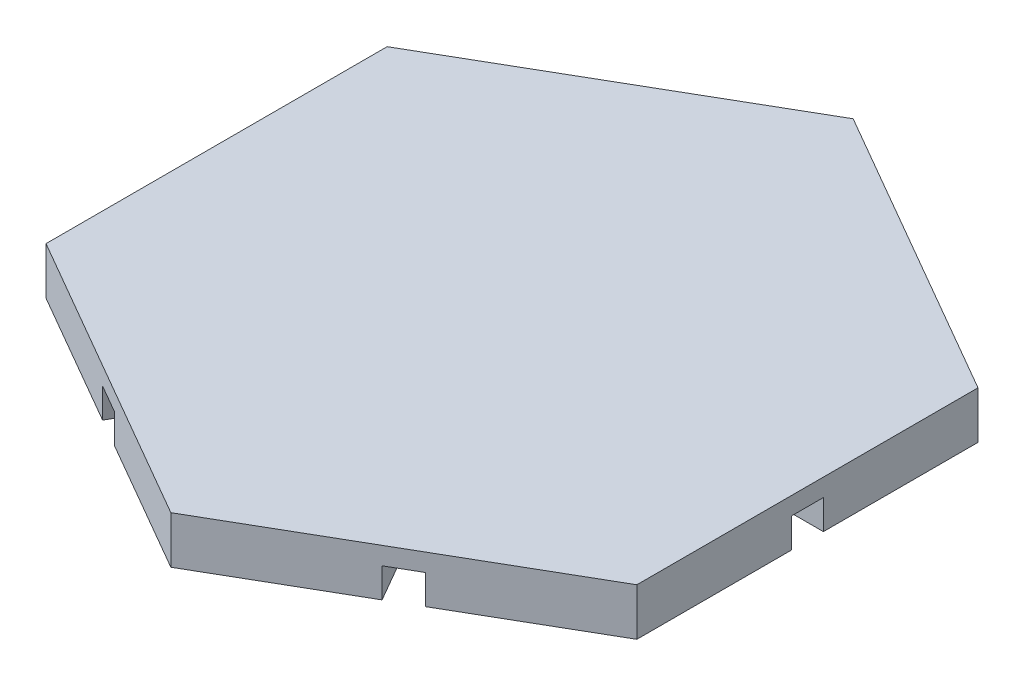
SolidWorks part; units mm, degrees
material "PET"
ref_plane "Front Plane" through (0, 0, 0) normal (0, 0, 1) x (1, 0, 0)
ref_plane "Top Plane" through (0, 0, 0) normal (0, 1, 0) x (1, 0, 0)
ref_plane "Right Plane" through (0, 0, 0) normal (1, 0, 0) x (0, 0, -1)
sketch "Sketch1" plane through (0, 0, 0) normal (0, 1, 0) x (1, 0, 0)
  line L0 (25, 43.3013) -> (-25, -43.3013) construction
  line L1 (0, 57.735) -> (-50, 28.8675)
  line L2 (-50, 28.8675) -> (-50, -28.8675)
  line L3 (-50, -28.8675) -> (0, -57.735)
  line L4 (0, -57.735) -> (50, -28.8675)
  line L5 (50, -28.8675) -> (50, 28.8675)
  line L6 (50, 28.8675) -> (0, 57.735)
  circle A0 centre (0, 0) radius 50 construction
  dimension "D2" = 100
extrude "Boss-Extrude1" add sketch "Sketch1" along normal blind 8
sketch "Sketch2" plane through (0, 0, 0) normal (0, -1, 0) x (1, 0, 0)
  line L0 (-25, 43.3013) -> (25, -43.3013)
  line L1 (-50, 28.8675) -> (0, 57.735) construction
  line L2 (50, -28.8675) -> (0, -57.735) construction
  line L3 (25, 43.3013) -> (-25, -43.3013)
  line L4 (0, 57.735) -> (50, 28.8675) construction
  line L5 (0, -57.735) -> (-50, -28.8675) construction
  line L6 (50, 0) -> (-50, 0)
  line L7 (50, 28.8675) -> (50, -28.8675) construction
  line L8 (-50, -28.8675) -> (-50, 28.8675) construction
extrude "Cut-Extrude-Thin1" cut sketch "Sketch2" against normal blind 5 thin thin type mid plane wall 5.4
